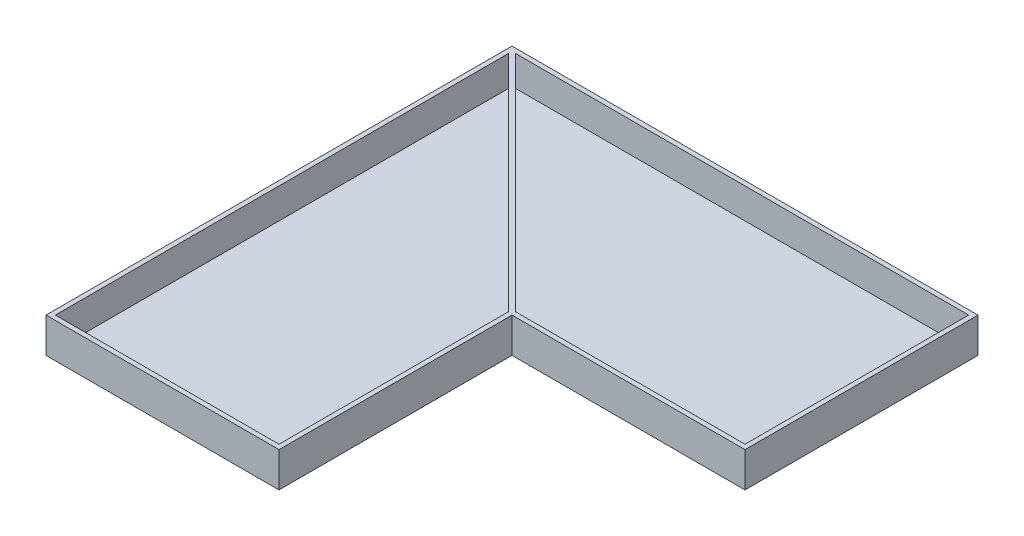
SolidWorks part; units mm, degrees
ref_plane "前视基准面" through (0, 0, 0) normal (0, 0, 1) x (1, 0, 0)
ref_plane "上视基准面" through (0, 0, 0) normal (0, 1, 0) x (1, 0, 0)
ref_plane "右视基准面" through (0, 0, 0) normal (1, 0, 0) x (0, 0, -1)
sketch "草图1" plane through (0, 0, 0) normal (0, 1, 0) x (1, 0, 0)
  line L2 (0, 0) -> (0, -2000)
  line L3 (0, -2000) -> (1000, -2000)
  line L4 (1000, -1000) -> (1000, -2000)
  line L5 (0, 0) -> (2000, 0)
  line L7 (1000, -1000) -> (2000, -1000)
  line L8 (2000, 0) -> (2000, -1000)
  point P3 (0, 0)
  point P9 (0, 0)
  point P10 (0, -647.9122)
  point P11 (0, 0)
  point P12 (0, 0)
  point P13 (0, 1055.4419)
  dimension "D1" = 1000
  dimension "D2" = 2000
  dimension "D3" = 1000
  dimension "D4" = 2000
extrude "凸台-拉伸1" add sketch "草图1" along normal blind 20
sketch "草图3" plane through (0, 20, 0) normal (0, 1, 0) x (1, 0, 0)
  line L0 (0, -2000) -> (1000, -2000) construction
  line L1 (1000, -2000) -> (1000, -1000) construction
  line L2 (1000, -1000) -> (2000, -1000) construction
  line L3 (2000, -1000) -> (2000, 0) construction
  line L4 (2000, 0) -> (0, 0) construction
  line L5 (0, 0) -> (0, -2000) construction
  line L6 (0, -2000) -> (1000, -2000)
  line L7 (1000, -2000) -> (1000, -1000)
  line L8 (1000, -1000) -> (2000, -1000)
  line L9 (2000, -1000) -> (2000, 0)
  line L10 (2000, 0) -> (0, 0)
  line L11 (0, 0) -> (0, -2000)
  line L12 (20, -34.1421) -> (20, -1980)
  line L13 (20, -1980) -> (980, -1980)
  line L14 (980, -1980) -> (980, -994.1421)
  line L15 (994.1421, -980) -> (1980, -980)
  line L16 (1980, -980) -> (1980, -20)
  line L17 (1980, -20) -> (34.1421, -20)
  line L18 (20, -20) -> (980, -980) construction
  line L19 (20, -34.1421) -> (980, -994.1421)
  line L20 (34.1421, -20) -> (994.1421, -980)
  line L21 (7.0711, 7.0711) -> (1007.0711, -992.9289) construction
  line L22 (0, 0) -> (1000, -1000) construction
  line L23 (-7.0711, -7.0711) -> (992.9289, -1007.0711) construction
  line L24 (20, -20) -> (20, -1980) construction
  line L25 (1980, -20) -> (20, -20) construction
  line L26 (980, -980) -> (1980, -980) construction
  line L27 (980, -1980) -> (980, -980) construction
  dimension "D1" = 20
  dimension "D2" = 10
  dimension "D3" = 10
extrude "凸台-拉伸2" add sketch "草图3" along normal blind 130
